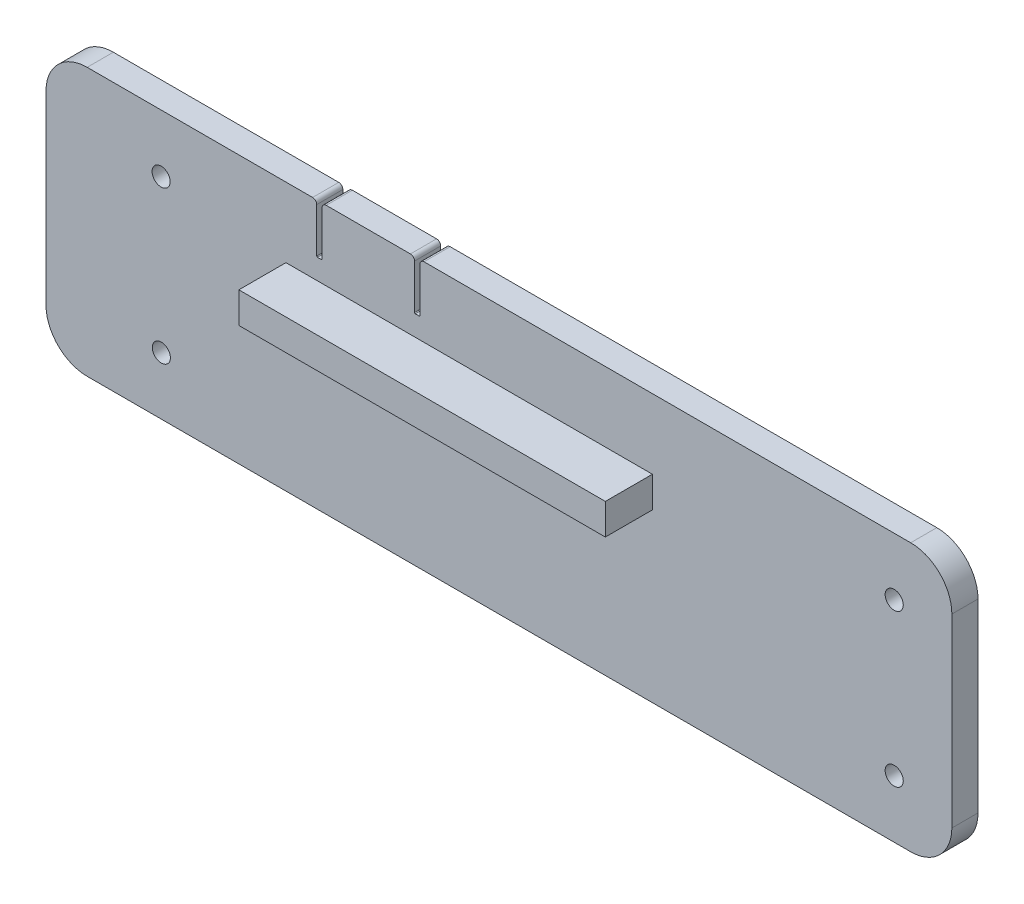
SolidWorks part; units mm, degrees
ref_plane "Front Plane" through (0, 0, 0) normal (0, 0, 1) x (1, 0, 0)
ref_plane "Top Plane" through (0, 0, 0) normal (0, 1, 0) x (1, 0, 0)
ref_plane "Right Plane" through (0, 0, 0) normal (1, 0, 0) x (0, 0, -1)
sketch "Model"
sketch3d "3DSketch1"
  line L0 (600.4778, 523.5934, 0) -> (600.4778, 568.5934, 0) construction
  line L1 (610.4778, 513.5934, 0) -> (810.4778, 513.5934, 0) construction
  line L2 (820.4778, 523.5934, 0) -> (820.4778, 568.5934, 0) construction
  line L3 (692.2831, 578.5934, 0) -> (810.4778, 578.5934, 0) construction
  line L4 (691.2831, 566.7934, 0) -> (691.2831, 577.5934, 0) construction
  line L5 (690.1831, 566.5934, 0) -> (691.0831, 566.5934, 0) construction
  line L6 (689.9831, 566.7934, 0) -> (689.9831, 577.5934, 0) construction
  line L7 (668.5281, 578.5934, 0) -> (688.9831, 578.5934, 0) construction
  line L8 (667.5281, 566.7934, 0) -> (667.5281, 577.5934, 0) construction
  line L9 (666.4281, 566.5934, 0) -> (667.3281, 566.5934, 0) construction
  line L10 (666.2281, 566.7934, 0) -> (666.2281, 577.5934, 0) construction
  line L11 (610.4778, 578.5934, 0) -> (665.2281, 578.5934, 0) construction
  line L12 (600.4778, 523.5934, 0) -> (600.4778, 568.5934, 0)
  line L13 (610.4778, 513.5934, 0) -> (810.4778, 513.5934, 0)
  line L14 (820.4778, 523.5934, 0) -> (820.4778, 568.5934, 0)
  line L15 (692.2831, 578.5934, 0) -> (810.4778, 578.5934, 0)
  line L16 (691.2831, 566.7934, 0) -> (691.2831, 577.5934, 0)
  line L17 (690.1831, 566.5934, 0) -> (691.0831, 566.5934, 0)
  line L18 (689.9831, 566.7934, 0) -> (689.9831, 577.5934, 0)
  line L19 (668.5281, 578.5934, 0) -> (688.9831, 578.5934, 0)
  line L20 (667.5281, 566.7934, 0) -> (667.5281, 577.5934, 0)
  line L21 (666.4281, 566.5934, 0) -> (667.3281, 566.5934, 0)
  line L22 (666.2281, 566.7934, 0) -> (666.2281, 577.5934, 0)
  line L23 (610.4778, 578.5934, 0) -> (665.2281, 578.5934, 0)
  arc A0 (600.4778, 523.5934, 0) -> (610.4778, 513.5934, 0) centre (610.4778, 523.5934, 0) ccw construction
  arc A1 (810.4778, 513.5934, 0) -> (820.4778, 523.5934, 0) centre (810.4778, 523.5934, 0) ccw construction
  arc A2 (820.4778, 568.5934, 0) -> (810.4778, 578.5934, 0) centre (810.4778, 568.5934, 0) ccw construction
  arc A3 (692.2831, 578.5934, 0) -> (691.2831, 577.5934, 0) centre (692.2831, 577.5934, 0) ccw construction
  arc A4 (691.0831, 566.5934, 0) -> (691.2831, 566.7934, 0) centre (691.0831, 566.7934, 0) ccw construction
  arc A5 (689.9831, 566.7934, 0) -> (690.1831, 566.5934, 0) centre (690.1831, 566.7934, 0) ccw construction
  arc A6 (689.9831, 577.5934, 0) -> (688.9831, 578.5934, 0) centre (688.9831, 577.5934, 0) ccw construction
  arc A7 (668.5281, 578.5934, 0) -> (667.5281, 577.5934, 0) centre (668.5281, 577.5934, 0) ccw construction
  arc A8 (667.3281, 566.5934, 0) -> (667.5281, 566.7934, 0) centre (667.3281, 566.7934, 0) ccw construction
  arc A9 (666.2281, 566.7934, 0) -> (666.4281, 566.5934, 0) centre (666.4281, 566.7934, 0) ccw construction
  arc A10 (666.2281, 577.5934, 0) -> (665.2281, 578.5934, 0) centre (665.2281, 577.5934, 0) ccw construction
  arc A11 (610.4778, 578.5934, 0) -> (600.4778, 568.5934, 0) centre (610.4778, 568.5934, 0) ccw construction
  arc A12 (600.4778, 523.5934, 0) -> (610.4778, 513.5934, 0) centre (610.4778, 523.5934, 0) ccw
  arc A13 (810.4778, 513.5934, 0) -> (820.4778, 523.5934, 0) centre (810.4778, 523.5934, 0) ccw
  arc A14 (820.4778, 568.5934, 0) -> (810.4778, 578.5934, 0) centre (810.4778, 568.5934, 0) ccw
  arc A15 (692.2831, 578.5934, 0) -> (691.2831, 577.5934, 0) centre (692.2831, 577.5934, 0) ccw
  arc A16 (691.0831, 566.5934, 0) -> (691.2831, 566.7934, 0) centre (691.0831, 566.7934, 0) ccw
  arc A17 (689.9831, 566.7934, 0) -> (690.1831, 566.5934, 0) centre (690.1831, 566.7934, 0) ccw
  arc A18 (689.9831, 577.5934, 0) -> (688.9831, 578.5934, 0) centre (688.9831, 577.5934, 0) ccw
  arc A19 (668.5281, 578.5934, 0) -> (667.5281, 577.5934, 0) centre (668.5281, 577.5934, 0) ccw
  arc A20 (667.3281, 566.5934, 0) -> (667.5281, 566.7934, 0) centre (667.3281, 566.7934, 0) ccw
  arc A21 (666.2281, 566.7934, 0) -> (666.4281, 566.5934, 0) centre (666.4281, 566.7934, 0) ccw
  arc A22 (666.2281, 577.5934, 0) -> (665.2281, 578.5934, 0) centre (665.2281, 577.5934, 0) ccw
  arc A23 (610.4778, 578.5934, 0) -> (600.4778, 568.5934, 0) centre (610.4778, 568.5934, 0) ccw
  point P3 (610.4778, 523.5934, 10)
  point P5 (610.4778, 523.5934, 10)
  point P6 (810.4778, 523.5934, 10)
  point P9 (810.4778, 568.5934, 10)
  point P11 (810.4778, 523.5934, 10)
  point P12 (692.2831, 577.5934, 1)
  point P15 (691.0831, 566.7934, 0.2)
  point P17 (810.4778, 568.5934, 10)
  point P19 (690.1831, 566.7934, 0.2)
  point P21 (688.9831, 577.5934, 1)
  point P23 (692.2831, 577.5934, 1)
  point P25 (668.5281, 577.5934, 1)
  point P28 (667.3281, 566.7934, 0.2)
  point P29 (691.0831, 566.7934, 0.2)
  point P31 (666.4281, 566.7934, 0.2)
  point P34 (665.2281, 577.5934, 1)
  point P35 (690.1831, 566.7934, 0.2)
  point P36 (610.4778, 568.5934, 10)
  point P41 (688.9831, 577.5934, 1)
  point P47 (668.5281, 577.5934, 1)
  point P53 (667.3281, 566.7934, 0.2)
  point P57 (666.4281, 566.7934, 0.2)
  point P65 (665.2281, 577.5934, 1)
  point P71 (610.4778, 568.5934, 10)
  dimension "D1" = 220
ref_plane "Plane1" through (0, 0, 2.54) normal (0, 0, 1) x (1, 0, 0)
extrude "Boss-Extrude1" add sketch "3DSketch1" along direction (0, 0, 1) on the side against the normal blind 6.35 from surface at 0 contours L12 A23 L23 A22 L22 A21 L21 A20 L20 A19 L19 A18 L18 A17 L17 A16 L16 A15 L15 A14 L14 A13 L13 A12
sketch "Sketch2" plane through (0, 0, 0) normal (0, 0, 1) x (1, 0, 0)
  circle A0 centre (806.4778, 527.5934) radius 2.2 construction
  circle A1 centre (806.4778, 564.5934) radius 2.2 construction
  circle A2 centre (628.4914, 527.5934) radius 2.2 construction
  circle A3 centre (628.4378, 564.5934) radius 2.2 construction
  circle A4 centre (806.4778, 527.5934) radius 2.2
  circle A5 centre (806.4778, 564.5934) radius 2.2
  circle A6 centre (628.4914, 527.5934) radius 2.2
  circle A7 centre (628.4378, 564.5934) radius 2.2
extrude "Cut-Extrude1" cut sketch "Sketch2" against normal through all
sketch "Sketch3" plane through (0, 0, 0) normal (0, 0, 1) x (1, 0, 0)
  line L1 (658.7502, 561.6434) -> (747.7502, 561.6434)
  line L2 (658.7502, 561.6434) -> (658.7502, 554.1434)
  line L3 (658.7502, 554.1434) -> (747.7502, 554.1434)
  line L4 (747.7502, 561.6434) -> (747.7502, 554.1434)
extrude "Boss-Extrude2" add sketch "Sketch3" along normal blind 11.43
